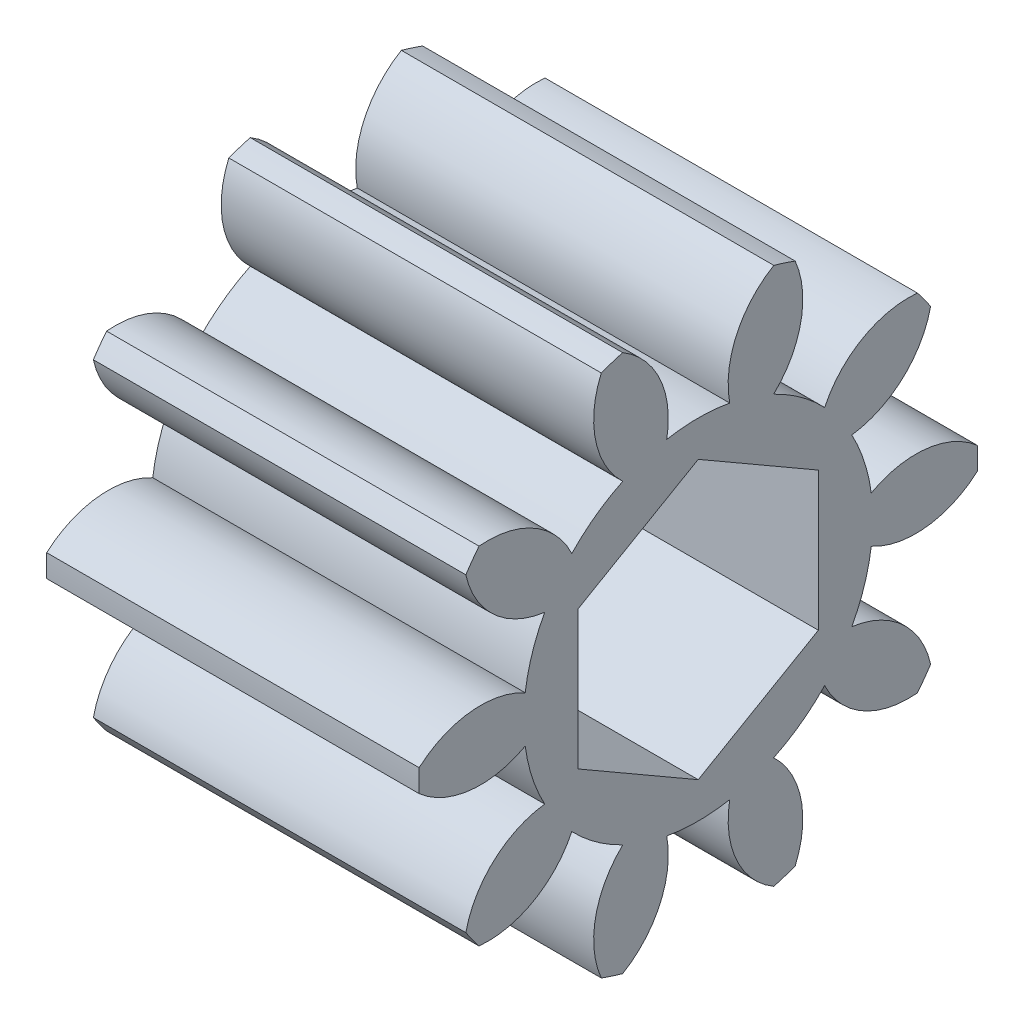
SolidWorks part; units mm, degrees
ref_plane "Plane1" through (0, 0, 0) normal (0, 0, 1) x (1, 0, 0)
ref_plane "Plane2" through (0, 0, 0) normal (0, 1, 0) x (1, 0, 0)
ref_plane "Plane3" through (0, 0, 0) normal (1, 0, 0) x (0, 0, -1)
other "Configuration Table"
sketch "HoldingSke" plane through (0, 0, 0) normal (0, 1, 0) x (1, 0, 0)
  line L0 (0, 0) -> (0.3939, -0.0695)
  line L1 (-15, 0) -> (100, 0) construction
  line L2 (0, 0) -> (-2.1039, 2.3779)
  line L3 (0, 0) -> (-11.863, 4.5341)
  line L4 (0, 0) -> (8.5048, 1.4996)
  line L5 (0, 0) -> (-46.8476, -17.4728)
  line L6 (0, 0) -> (-11.6055, -7.8303)
  line L7 (-2.1039, 2.3779) -> (8.6586, 51.2059)
  line L8 (-76.2, 54.61) -> (-74.4, 54.61)
  line L9 (-67.7845, 28.3722) -> (-49.3413, 33.142)
  line L10 (-76.2, 71.12) -> (104.1128, 71.12)
  line L11 (0, 0) -> (-14, 0)
  line L12 (-76.2, 101.6) -> (-76.113, 101.6)
  line L13 (24.9733, 27.94) -> (52.9518, 28.4284)
  line L14 (24.9733, 27.94) -> (24.9743, 27.94)
  line L15 (24.9733, 27.94) -> (100.4006, 29.5858)
  line L16 (-63.627, -2.5) -> (-12.827, -2.5)
  circle A0 centre (0, 0) radius 5
  circle A1 centre (0, 0) radius 9.374
  circle A2 centre (0, 0) radius 37.5
  circle A3 centre (0, 0) radius 5
  dimension "MHD" = 18.748
  dimension "Hub_dia" = 75
  dimension "Bore" = 10
  dimension "MBD" = 10
  dimension "Num_teeth" = 10
  dimension "Pitch" = 0.4
  dimension "Overall_len" = 50
  dimension "Show_teeth" = 10
  dimension "Thickness" = 14
  dimension "OAL" = 50.0001
  dimension "T_dim" = 1.8
  dimension "Ap" = 14.5
  dimension "H" = 19.05
  dimension "Pitch_radius" = 180.3128
  dimension "Width" = 14
  dimension "Backlash" = 0.087
  dimension "Addendum_fac" = 1
  dimension "Dedendum_fac" = 1.25
  dimension "Clearance_fac" = 0.25
  dimension "Dedendum_add" = 0.001
  dimension "Module" = 2.5
sketch "BasProSke" plane through (0, 0, 0) normal (0, 1, 0) x (1, 0, 0)
  line L0 (-10, 0) -> (60, 0) construction
  line L1 (0, 0) -> (0, 15)
  line L2 (0, 0) -> (14, 0)
  line L3 (14, 0) -> (14, 15)
  line L4 (14, 15) -> (0, 15)
  dimension "Thickness" = 14
  dimension "Diameter" = 30
revolve "Base-Revolve" add sketch "BasProSke" angle 360 about L0
sketch "TooCutSke" plane through (0, 0, 0) normal (1, 0, 0) x (0, 0, -1)
  line L1 (0, 0) -> (0, 107) construction
  line L2 (0, 0) -> (-2.1074, 12.3211) construction
  line L3 (0, 0) -> (-7.6446, 23.5277) construction
  line L4 (-2.1074, 12.3211) -> (-3.8223, 11.7639) construction
  arc A0 (1.6916, 9.2201) -> (-1.6916, 9.2201) centre (0, 0) ccw
  arc A1 (4.0875, 14.4587) -> (-4.0875, 14.4587) centre (0, 0) ccw
  circle A2 centre (0, 0) radius 12.5 construction
  circle A3 centre (0, 0) radius 12.1018 construction
  arc A4 (-1.6916, 9.2201) -> (-4.0875, 14.4587) centre (-6.6064, 10.1395) ccw
  arc A5 (4.0875, 14.4587) -> (1.6916, 9.2201) centre (6.6064, 10.1395) ccw
  dimension "Root_dia" = 18.748
  dimension "Overcut_dia" = 30.0508
  dimension "Pitch_dia" = 25
  dimension "Base_dia" = 24.2037
  dimension "Flank_rad" = 5
  dimension "Half_ang" = 18
  dimension "Half_CT" = 1.8032
extrude "ToothCut" cut sketch "TooCutSke" along normal through all
fillet "Breaks" [suppressed] radius 0.05
fillet "RootFillets" [suppressed] radius 0.626
pattern_circular "TeethCuts" count 10 every 36 about axis through (-10, 0, 0) along (1, 0, 0) of "ToothCut", "RootFillets", "Breaks"
sketch "HubNeaOneSke" plane through (0, 0, 0) normal (-1, 0, 0) x (0, 0, 1)
  circle A0 centre (0, 0) radius 9.374
  dimension "Diameter" = 18.748
extrude "HubNearOne" [suppressed] add sketch "HubNeaOneSke" along normal blind 36.0001
sketch "HubNeaBotSke" plane through (0, 0, 0) normal (-1, 0, 0) x (0, 0, 1)
  circle A0 centre (0, 0) radius 9.374
  dimension "Diameter" = 18.748
extrude "HubNearBoth" [suppressed] add sketch "HubNeaBotSke" along normal blind 18
ref_plane "FarPln" through (14, 0, 0) normal (1, 0, 0) x (0, 0, -1)
sketch "HubFarSke" plane through (14, 0, 0) normal (1, 0, 0) x (0, 0, -1)
  circle A0 centre (0, 0) radius 9.374
  dimension "Diameter" = 18.748
extrude "HubFar" [suppressed] add sketch "HubFarSke" along normal blind 18
sketch "BorSke" plane through (0, 0, 0) normal (1, 0, 0) x (0, 0, -1)
  circle A0 centre (0, 0) radius 5
  dimension "Diameter" = 10
extrude "Bore" cut sketch "BorSke" along normal mid plane 100.0001
sketch "KeySke" plane through (0, 0, 0) normal (1, 0, 0) x (0, 0, -1)
  line L0 (-2, 0) -> (-2, 6.8)
  line L1 (-2, 6.8) -> (2, 6.8)
  line L2 (2, 6.8) -> (2, 0)
  line L3 (0, 0) -> (0, 34) construction
  line L4 (-2, 0) -> (2, 0)
  dimension "Offset" = 6.8
  dimension "Width" = 4
extrude "Keyway" [suppressed] cut sketch "KeySke" along normal mid plane 100.0001
pattern_circular "Keyway2" [suppressed] count 2 every 90 about axis through (-10, 0, 0) along (1, 0, 0)
sketch "Sketch1" plane through (14, 0, 0) normal (1, 0, 0) x (0, 0, -1)
  line L1 (0, -7.4478) -> (6.45, -3.7239)
  line L2 (6.45, -3.7239) -> (6.45, 3.7239)
  line L3 (6.45, 3.7239) -> (0, 7.4478)
  line L4 (0, 7.4478) -> (-6.45, 3.7239)
  line L5 (-6.45, 3.7239) -> (-6.45, -3.7239)
  line L6 (-6.45, -3.7239) -> (0, -7.4478)
  circle A0 centre (0, 0) radius 6.45 construction
extrude "Cut-Extrude1" cut sketch "Sketch1" against normal through all
sketch "Sketch2" plane through (14, 0, 0) normal (1, 0, 0) x (0, 0, -1)
  line L0 (-6.45, -3.7239) -> (0, -7.4478)
  line L1 (-6.45, -3.7239) -> (0, -7.4478)
  line L2 (0, -7.4478) -> (6.45, -3.7239)
  line L3 (0, -7.4478) -> (6.45, -3.7239)
  line L4 (6.45, -3.7239) -> (6.45, 3.7239)
  line L5 (6.45, -3.7239) -> (6.45, 3.7239)
  line L6 (6.45, 3.7239) -> (0, 7.4478)
  line L7 (6.45, 3.7239) -> (0, 7.4478)
  line L8 (0, 7.4478) -> (-6.45, 3.7239)
  line L9 (0, 7.4478) -> (-6.45, 3.7239)
  line L10 (-6.45, 3.7239) -> (-6.45, -3.7239)
  line L11 (-6.45, 3.7239) -> (-6.45, -3.7239)
  arc A0 (14.9878, -0.6039) -> (14.9878, 0.6039) centre (0, 0) ccw
  arc A1 (14.9878, -0.6039) -> (14.9878, 0.6039) centre (0, 0) ccw
  arc A2 (9.2916, -1.2403) -> (14.9878, -0.6039) centre (11.6848, 3.1497) ccw
  arc A3 (9.2916, -1.2403) -> (14.9878, -0.6039) centre (11.6848, 3.1497) ccw
  arc A4 (8.2461, -4.458) -> (9.2916, -1.2403) centre (0, 0) ccw
  arc A5 (8.2461, -4.458) -> (9.2916, -1.2403) centre (0, 0) ccw
  arc A6 (12.4804, -8.3211) -> (8.2461, -4.458) centre (7.6018, -9.4163) ccw
  arc A7 (12.4804, -8.3211) -> (8.2461, -4.458) centre (7.6018, -9.4163) ccw
  arc A8 (11.7705, -9.2982) -> (12.4804, -8.3211) centre (0, 0) ccw
  arc A9 (11.7705, -9.2982) -> (12.4804, -8.3211) centre (0, 0) ccw
  arc A10 (6.788, -6.4649) -> (11.7705, -9.2982) centre (11.3045, -4.3199) ccw
  arc A11 (6.788, -6.4649) -> (11.7705, -9.2982) centre (11.3045, -4.3199) ccw
  arc A12 (4.0509, -8.4535) -> (6.788, -6.4649) centre (0, 0) ccw
  arc A13 (4.0509, -8.4535) -> (6.788, -6.4649) centre (0, 0) ccw
  arc A14 (5.2058, -14.0677) -> (4.0509, -8.4535) centre (0.6152, -12.0862) ccw
  arc A15 (5.2058, -14.0677) -> (4.0509, -8.4535) centre (0.6152, -12.0862) ccw
  arc A16 (4.0572, -14.4409) -> (5.2058, -14.0677) centre (0, 0) ccw
  arc A17 (4.0572, -14.4409) -> (5.2058, -14.0677) centre (0, 0) ccw
  arc A18 (1.6916, -9.2201) -> (4.0572, -14.4409) centre (6.6064, -10.1395) ccw
  arc A19 (1.6916, -9.2201) -> (4.0572, -14.4409) centre (6.6064, -10.1395) ccw
  arc A20 (-1.6916, -9.2201) -> (1.6916, -9.2201) centre (0, 0) ccw
  arc A21 (-1.6916, -9.2201) -> (1.6916, -9.2201) centre (0, 0) ccw
  arc A22 (-4.0572, -14.4409) -> (-1.6916, -9.2201) centre (-6.6064, -10.1395) ccw
  arc A23 (-4.0572, -14.4409) -> (-1.6916, -9.2201) centre (-6.6064, -10.1395) ccw
  arc A24 (-5.2058, -14.0677) -> (-4.0572, -14.4409) centre (0, 0) ccw
  arc A25 (-5.2058, -14.0677) -> (-4.0572, -14.4409) centre (0, 0) ccw
  arc A26 (-4.0509, -8.4535) -> (-5.2058, -14.0677) centre (-0.6152, -12.0862) ccw
  arc A27 (-4.0509, -8.4535) -> (-5.2058, -14.0677) centre (-0.6152, -12.0862) ccw
  arc A28 (-6.788, -6.4649) -> (-4.0509, -8.4535) centre (0, 0) ccw
  arc A29 (-6.788, -6.4649) -> (-4.0509, -8.4535) centre (0, 0) ccw
  arc A30 (-11.7705, -9.2982) -> (-6.788, -6.4649) centre (-11.3045, -4.3199) ccw
  arc A31 (-11.7705, -9.2982) -> (-6.788, -6.4649) centre (-11.3045, -4.3199) ccw
  arc A32 (-12.4804, -8.3211) -> (-11.7705, -9.2982) centre (0, 0) ccw
  arc A33 (-12.4804, -8.3211) -> (-11.7705, -9.2982) centre (0, 0) ccw
  arc A34 (-8.2461, -4.458) -> (-12.4804, -8.3211) centre (-7.6018, -9.4163) ccw
  arc A35 (-8.2461, -4.458) -> (-12.4804, -8.3211) centre (-7.6018, -9.4163) ccw
  arc A36 (-9.2916, -1.2403) -> (-8.2461, -4.458) centre (0, 0) ccw
  arc A37 (-9.2916, -1.2403) -> (-8.2461, -4.458) centre (0, 0) ccw
  arc A38 (-14.9878, -0.6039) -> (-9.2916, -1.2403) centre (-11.6848, 3.1497) ccw
  arc A39 (-14.9878, -0.6039) -> (-9.2916, -1.2403) centre (-11.6848, 3.1497) ccw
  arc A40 (-14.9878, 0.6039) -> (-14.9878, -0.6039) centre (0, 0) ccw
  arc A41 (-14.9878, 0.6039) -> (-14.9878, -0.6039) centre (0, 0) ccw
  arc A42 (-9.2916, 1.2403) -> (-14.9878, 0.6039) centre (-11.6848, -3.1497) ccw
  arc A43 (-9.2916, 1.2403) -> (-14.9878, 0.6039) centre (-11.6848, -3.1497) ccw
  arc A44 (-8.2461, 4.458) -> (-9.2916, 1.2403) centre (0, 0) ccw
  arc A45 (-8.2461, 4.458) -> (-9.2916, 1.2403) centre (0, 0) ccw
  arc A46 (-12.4804, 8.3211) -> (-8.2461, 4.458) centre (-7.6018, 9.4163) ccw
  arc A47 (-12.4804, 8.3211) -> (-8.2461, 4.458) centre (-7.6018, 9.4163) ccw
  arc A48 (-11.7705, 9.2982) -> (-12.4804, 8.3211) centre (0, 0) ccw
  arc A49 (-11.7705, 9.2982) -> (-12.4804, 8.3211) centre (0, 0) ccw
  arc A50 (-6.788, 6.4649) -> (-11.7705, 9.2982) centre (-11.3045, 4.3199) ccw
  arc A51 (-6.788, 6.4649) -> (-11.7705, 9.2982) centre (-11.3045, 4.3199) ccw
  arc A52 (-4.0509, 8.4535) -> (-6.788, 6.4649) centre (0, 0) ccw
  arc A53 (-4.0509, 8.4535) -> (-6.788, 6.4649) centre (0, 0) ccw
  arc A54 (-5.2058, 14.0677) -> (-4.0509, 8.4535) centre (-0.6152, 12.0862) ccw
  arc A55 (-5.2058, 14.0677) -> (-4.0509, 8.4535) centre (-0.6152, 12.0862) ccw
  arc A56 (-4.0572, 14.4409) -> (-5.2058, 14.0677) centre (0, 0) ccw
  arc A57 (-4.0572, 14.4409) -> (-5.2058, 14.0677) centre (0, 0) ccw
  arc A58 (-1.6916, 9.2201) -> (-4.0572, 14.4409) centre (-6.6064, 10.1395) ccw
  arc A59 (-1.6916, 9.2201) -> (-4.0572, 14.4409) centre (-6.6064, 10.1395) ccw
  arc A60 (1.6916, 9.2201) -> (-1.6916, 9.2201) centre (0, 0) ccw
  arc A61 (1.6916, 9.2201) -> (-1.6916, 9.2201) centre (0, 0) ccw
  arc A62 (4.0572, 14.4409) -> (1.6916, 9.2201) centre (6.6064, 10.1395) ccw
  arc A63 (4.0572, 14.4409) -> (1.6916, 9.2201) centre (6.6064, 10.1395) ccw
  arc A64 (5.2058, 14.0677) -> (4.0572, 14.4409) centre (0, 0) ccw
  arc A65 (5.2058, 14.0677) -> (4.0572, 14.4409) centre (0, 0) ccw
  arc A66 (4.0509, 8.4535) -> (5.2058, 14.0677) centre (0.6152, 12.0862) ccw
  arc A67 (4.0509, 8.4535) -> (5.2058, 14.0677) centre (0.6152, 12.0862) ccw
  arc A68 (6.788, 6.4649) -> (4.0509, 8.4535) centre (0, 0) ccw
  arc A69 (6.788, 6.4649) -> (4.0509, 8.4535) centre (0, 0) ccw
  arc A70 (11.7705, 9.2982) -> (6.788, 6.4649) centre (11.3045, 4.3199) ccw
  arc A71 (11.7705, 9.2982) -> (6.788, 6.4649) centre (11.3045, 4.3199) ccw
  arc A72 (12.4804, 8.3211) -> (11.7705, 9.2982) centre (0, 0) ccw
  arc A73 (12.4804, 8.3211) -> (11.7705, 9.2982) centre (0, 0) ccw
  arc A74 (8.2461, 4.458) -> (12.4804, 8.3211) centre (7.6018, 9.4163) ccw
  arc A75 (8.2461, 4.458) -> (12.4804, 8.3211) centre (7.6018, 9.4163) ccw
  arc A76 (9.2916, 1.2403) -> (8.2461, 4.458) centre (0, 0) ccw
  arc A77 (9.2916, 1.2403) -> (8.2461, 4.458) centre (0, 0) ccw
  arc A78 (14.9878, 0.6039) -> (9.2916, 1.2403) centre (11.6848, -3.1497) ccw
  arc A79 (14.9878, 0.6039) -> (9.2916, 1.2403) centre (11.6848, -3.1497) ccw
extrude "Boss-Extrude1" add sketch "Sketch2" along normal blind 6
equation "' \"Module@HoldingSke\" = 6.35"
equation "' \"Num_teeth@HoldingSke\" = 12"
equation "' \"Ap@HoldingSke\" =  20"
equation "' \"Ap@HoldingSke\" = 20"
equation "' \"Width@HoldingSke\" = 0.5 * 25.4"
equation "' \"Hub_dia@HoldingSke\"= 1 * 25.4"
equation "' \"Hub_dia@HoldingSke\" = 1 * 25.4"
equation "' \"Overall_len@HoldingSke\" = 1.0 * 25.4"
equation "' \"Bore@HoldingSke\" = 0.75 * 25.4"
equation "' \"T_dim@HoldingSke\" = 0.1 * 25.4"
equation "' \"Width@KeySke\" = 0.25 * 25.4"
equation "' \"Show_teeth@HoldingSke\" = 13"
equation "' \"Backlash@HoldingSke\" = 0.009 * 25.4"
equation "' \"Addendum_fac@HoldingSke\" = 1.0"
equation "' \"Dedendum_fac@HoldingSke\" = 1.25"
equation "' \"Dedendum_add@HoldingSke\" = 0.00005 * 25.4"
equation "' \"Clearance_fac@HoldingSke\" = 0.25"
equation "\"Pitch@HoldingSke\" = 1 / \"Module@HoldingSke\""
equation "\"Overcut_dia@TooCutSke\" = (\"Num_teeth@HoldingSke\" + 2 * \"Addendum_fac@HoldingSke\") / \"Pitch@HoldingSke\" + 0.002 * 25.4"
equation "\"Pitch_dia@TooCutSke\" = \"Num_teeth@HoldingSke\" / \"Pitch@HoldingSke\""
equation "\"Base_dia@TooCutSke\" = \"Num_teeth@HoldingSke\" / \"Pitch@HoldingSke\" * cos((\"Ap@HoldingSke\"  * 3.14159265 / 180))"
equation "\"Root_dia@TooCutSke\" = (\"Num_teeth@HoldingSke\" + 2) / \"Pitch@HoldingSke\" - 2 * (\"Addendum_fac@HoldingSke\" + \"Dedendum_fac@HoldingSke\") / \"Pitch@HoldingSke\" - \"Dedendum_add@HoldingSke\" * 2"
equation "\"Half_ang@TooCutSke\" = 180 / \"Num_teeth@HoldingSke\""
equation "\"Half_CT@TooCutSke\" = \"Num_teeth@HoldingSke\" / \"Pitch@HoldingSke\" * sin((3.14159265 / 2 / \"Num_teeth@HoldingSke\")) / 2 - 7 * \"Backlash@HoldingSke\" / 4"
equation "\"Flank_rad@TooCutSke\" = \"Num_teeth@HoldingSke\" / \"Pitch@HoldingSke\" / 5"
equation "\"Radius@RootFillets\" = \"Clearance_fac@HoldingSke\" / \"Pitch@HoldingSke\" + \"Dedendum_add@HoldingSke\""
equation "\"Break_rad@Breaks\" = 0.02 / \"Pitch@HoldingSke\""
equation "\"Thickness@HoldingSke\" = \"Width@HoldingSke\""
equation "\"OAL@HoldingSke\" = \"Thickness@HoldingSke\""
equation "\"MHD@HoldingSke\" = (\"Num_teeth@HoldingSke\" + 2) / \"Pitch@HoldingSke\" - 2 * (\"Addendum_fac@HoldingSke\" + \"Dedendum_fac@HoldingSke\")  / \"Pitch@HoldingSke\" - \"Dedendum_add@HoldingSke\" * 2"
equation "\"MBD@HoldingSke\" = (\"Num_teeth@HoldingSke\" + 2) / \"Pitch@HoldingSke\" - 2 * (\"Addendum_fac@HoldingSke\" + \"Dedendum_fac@HoldingSke\")  / \"Pitch@HoldingSke\" - \"Dedendum_add@HoldingSke\" * 2 - 0.002 * 25.4"
equation "\"MHD@HoldingSke\" = ((sgn( \"MHD@HoldingSke\" - \"Hub_dia@HoldingSke\" )-1)*( \"MHD@HoldingSke\" - \"Hub_dia@HoldingSke\" ))/-2+ \"Hub_dia@HoldingSke\""
equation "\"MBD@HoldingSke\" = ((sgn( \"MBD@HoldingSke\" - \"Bore@HoldingSke\" )-1)*( \"MBD@HoldingSke\" - \"Bore@HoldingSke\" ))/-2+ \"Bore@HoldingSke\""
equation "\"OAL@HoldingSke\" = ((sgn( \"OAL@HoldingSke\" - \"Overall_len@HoldingSke\" )+1)*( \"OAL@HoldingSke\" - \"Overall_len@HoldingSke\" ))/2 + \"Overall_len@HoldingSke\" + 0.000002 * 25.4"
equation "\"Num_teeth@TeethCuts\" = int( \"Show_teeth@HoldingSke\" ) + 1"
equation "\"Num_teeth@TeethCuts\" = ((sgn( \"Num_teeth@TeethCuts\" - \"Num_teeth@HoldingSke\" )-1)*( \"Num_teeth@TeethCuts\" - \"Num_teeth@HoldingSke\" ))/-2+ \"Num_teeth@HoldingSke\""
equation "\"Num_teeth@TeethCuts\" = ((sgn( \"Num_teeth@TeethCuts\" - 2.0)+1)*( \"Num_teeth@TeethCuts\" - 2.0))/2 +2.0"
equation "\"Angle@TeethCuts\" = 360.0 / \"Num_teeth@HoldingSke\""
equation "\"Diameter@BasProSke\" = (\"Num_teeth@HoldingSke\" + 2 * \"Addendum_fac@HoldingSke\") / \"Pitch@HoldingSke\""
equation "\"Thickness@BasProSke\"  = \"Thickness@HoldingSke\""
equation "' \"Fillet_rad@BasProSke\" =  \"Thickness@HoldingSke\" * 0.05"
equation "' \"Fillet_rad@BasProSke\" = \"Thickness@HoldingSke\" * 0.05"
equation "\"MHD@HoldingSke\" = ((sgn( \"MHD@HoldingSke\" - \"Root_dia@TooCutSke\" )-1)*( \"MHD@HoldingSke\" - \"Root_dia@TooCutSke\" ))/-2+ \"Root_dia@TooCutSke\""
equation "\"Diameter@HubNeaOneSke\" = \"MHD@HoldingSke\""
equation "\"Length@HubNearOne\" = \"OAL@HoldingSke\" - \"Thickness@BasProSke\""
equation "\"Diameter@HubNeaBotSke\" = \"MHD@HoldingSke\""
equation "\"Length@HubNearBoth\" = ( \"OAL@HoldingSke\" - \"Thickness@BasProSke\" ) / 2.0"
equation "\"Thickness@FarPln\" = \"Thickness@BasProSke\""
equation "\"Diameter@HubFarSke\" = \"MHD@HoldingSke\""
equation "\"Length@HubFar\" = ( \"OAL@HoldingSke\" - \"Thickness@BasProSke\" ) / 2.0"
equation "\"Diameter@BorSke\" = \"MBD@HoldingSke\""
equation "\"D1@Bore\" = \"OAL@HoldingSke\" * 2.0"
equation "\"D1@Keyway\" = \"OAL@HoldingSke\" * 2.0"
equation "\"Offset@KeySke\" = \"T_dim@HoldingSke\" + \"MBD@HoldingSke\" / 2.0"
